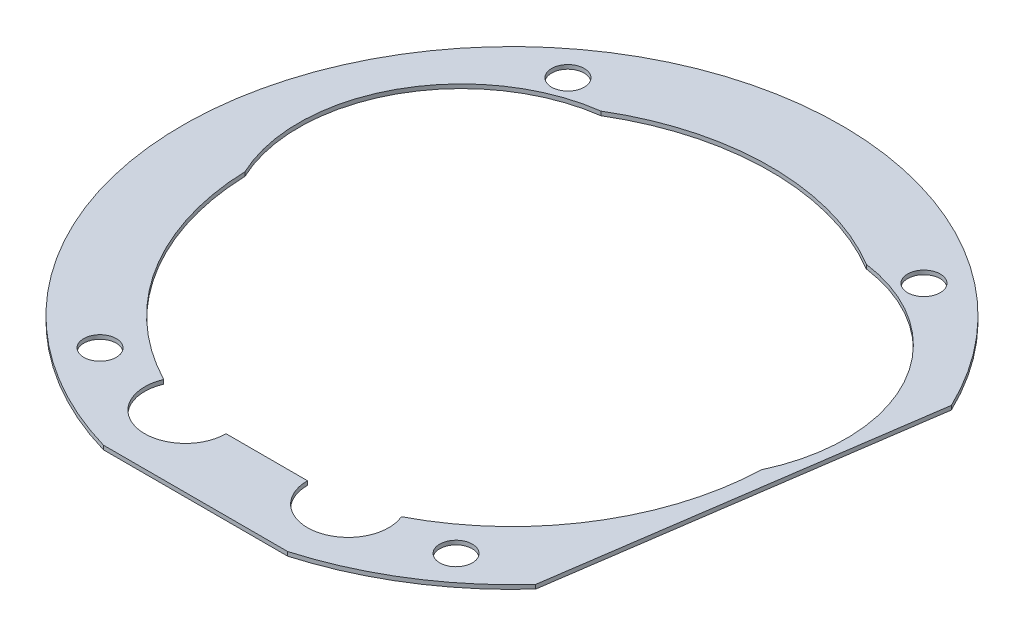
SolidWorks part; units mm, degrees
ref_plane "Front Plane" through (0, 0, 0) normal (0, 0, 1) x (1, 0, 0)
ref_plane "Top Plane" through (0, 0, 0) normal (0, 1, 0) x (1, 0, 0)
ref_plane "Right Plane" through (0, 0, 0) normal (1, 0, 0) x (0, 0, -1)
sketch "Sketch1" plane through (0, 0, 0) normal (0, 1, 0) x (1, 0, 0)
  line L1 (-4, -24.1073) -> (4, -24.1073)
  line L2 (29.2378, 13.961) -> (24.0491, -21.7118)
  line L3 (-9.0608, -31.1073) -> (9.0608, -31.1073)
  arc A0 (11.6854, -22.5524) -> (25.3854, -0.8615) centre (0, 0) ccw
  circle A1 centre (-17.5, 23) radius 1.6
  arc A2 (9.0608, -31.1073) -> (24.0491, -21.7118) centre (0, 0) ccw
  arc A3 (29.2378, 13.961) -> (-9.0608, -31.1073) centre (0, 0) ccw
  circle A4 centre (-17.5, -23) radius 1.6
  circle A5 centre (17.5, -23) radius 1.6
  circle A6 centre (17.5, 23) radius 1.6
  arc A7 (-4, -24.1073) -> (-11.6854, -22.5524) centre (-8, -24.1073) cw
  arc A8 (4, -24.1073) -> (11.6854, -22.5524) centre (8, -24.1073) ccw
  arc A9 (-25.3854, -0.8615) -> (-13.049, 21.7918) centre (-10.9014, 5.9366) cw
  arc A10 (13.049, 21.7918) -> (25.3854, -0.8615) centre (10.9014, 5.9366) cw
  arc A11 (-25.3854, -0.8615) -> (-11.6854, -22.5524) centre (0, 0) ccw
  arc A12 (13.049, 21.7918) -> (-13.049, 21.7918) centre (0, 0) ccw
  point P24 (-13.049, 21.7918)
  dimension "D1" = 3.2
  dimension "D2" = 3.2
  dimension "D3" = 3.2
  dimension "D4" = 3.2
  dimension "D10" = 7
  dimension "D11" = 25.4
  dimension "D12" = 32.4
  dimension "D15" = 4
  dimension "D16" = 4
  dimension "D20" = 30
  dimension "D21" = 16
  dimension "D22" = 16
  dimension "D5" = 17.5
  dimension "D6" = 23
  dimension "D7" = 46
  dimension "D8" = 35
  dimension "D9" = 7
  dimension "D13" = 16
  dimension "D14" = 36.0481
  dimension "D17" = 8
  dimension "D18" = 7.8411
  dimension "D19" = 7.8411
  dimension "D23" = 30
extrude "Boss-Extrude1" add sketch "Sketch1" along normal blind 0.4
